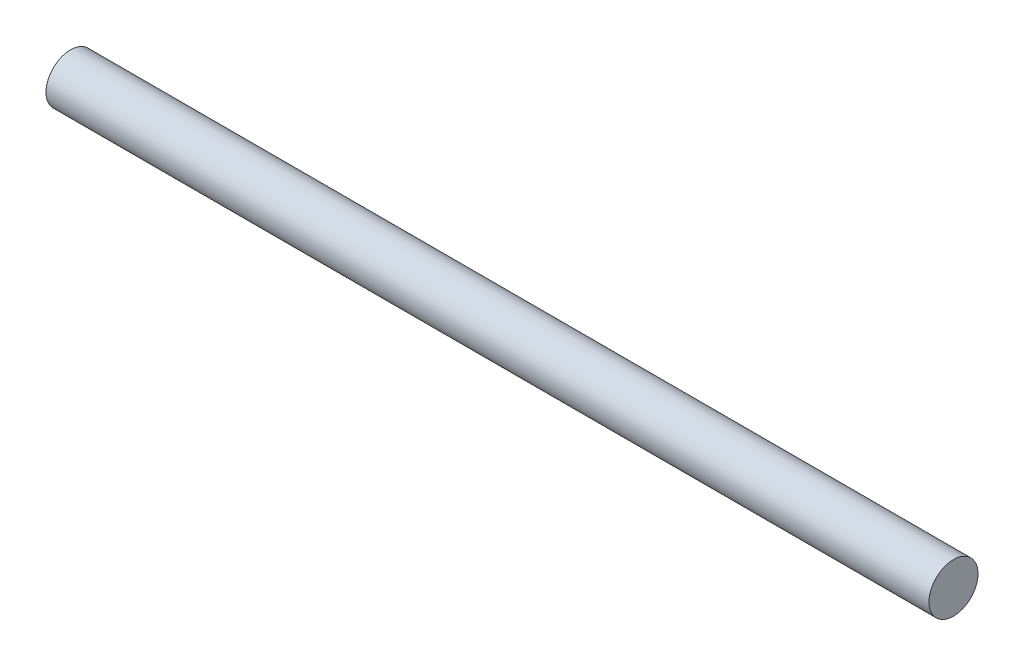
SolidWorks part; units mm, degrees
material "Plain Carbon Steel"
ref_plane "Front Plane" through (0, 0, 0) normal (0, 0, 1) x (1, 0, 0)
ref_plane "Top Plane" through (0, 0, 0) normal (0, 1, 0) x (1, 0, 0)
ref_plane "Right Plane" through (0, 0, 0) normal (1, 0, 0) x (0, 0, -1)
sketch "Sketch1" plane through (0, 0, 0) normal (1, 0, 0) x (0, 0, -1)
  circle A0 centre (0, 0) radius 2.5
  dimension "D1" = 5
extrude "Boss-Extrude1" add sketch "Sketch1" along normal blind 90
